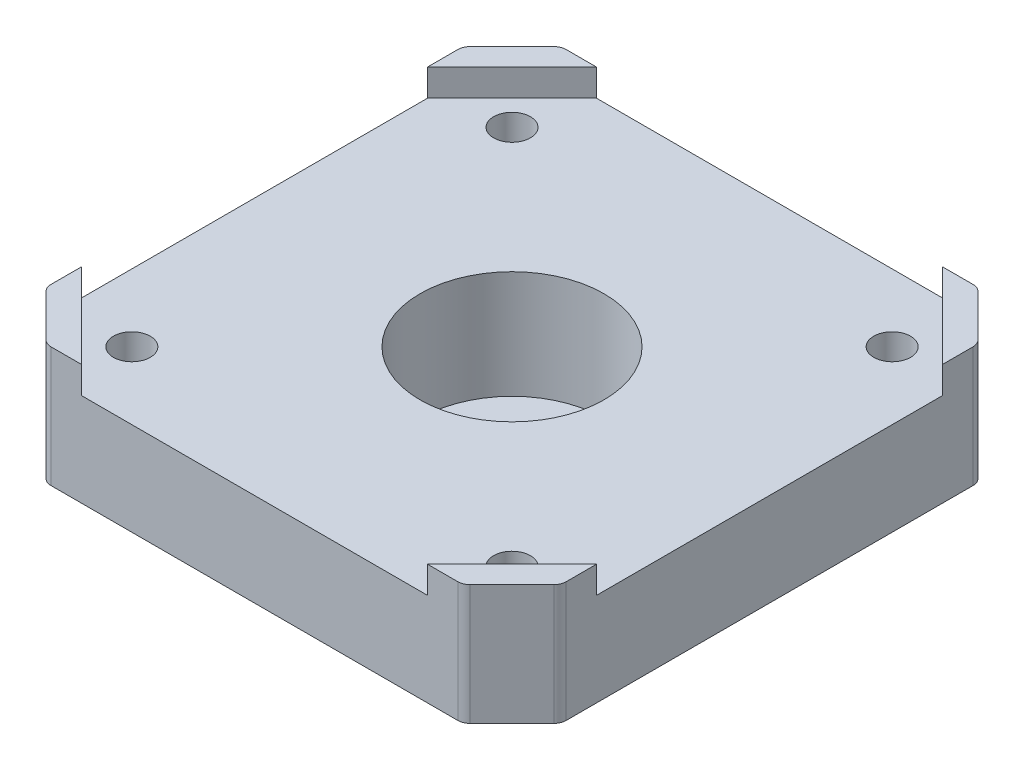
SolidWorks part; units mm, degrees
ref_plane "Alzado" through (0, 0, 0) normal (0, 0, 1) x (1, 0, 0)
ref_plane "Planta" through (0, 0, 0) normal (0, 1, 0) x (1, 0, 0)
ref_plane "Vista lateral" through (0, 0, 0) normal (1, 0, 0) x (0, 0, -1)
sketch "Croquis1" plane through (0, 0, 0) normal (0, 1, 0) x (1, 0, 0)
  line L0 (-21, 17) -> (-21, -17)
  line L1 (-21, -17) -> (-17, -21)
  line L2 (-17, -21) -> (17, -21)
  line L3 (17, -21) -> (21, -17)
  line L4 (21, -17) -> (21, 17)
  line L5 (21, 17) -> (17, 21)
  line L6 (17, 21) -> (-17, 21)
  line L7 (-17, 21) -> (-21, 17)
extrude "Saliente-Extruir1" add sketch "Croquis1" against normal blind 9.8
sketch "Croquis2" plane through (0, 0, 0) normal (0, 1, 0) x (-1, 0, 0)
  line L0 (-14.1008, -21) -> (14.1008, -21)
  line L1 (14.1008, -21) -> (21, -14.1008)
  line L2 (21, -14.1008) -> (21, 17)
  line L3 (21, 17) -> (17, 21)
  line L4 (17, 21) -> (-17, 21)
  line L5 (-17, 21) -> (-21, 17)
  line L6 (-21, 17) -> (-21, -14.1008)
  line L7 (-21, -14.1008) -> (-14.1008, -21)
extrude "Cortar-Extruir1" cut sketch "Croquis2" against normal blind 2.2
sketch "Croquis3" plane through (0, -2.2, 0) normal (0, 1, 0) x (-1, 0, 0)
  line L0 (-14.1008, 21) -> (-21, 14.1008)
  line L1 (-21, 14.1008) -> (-21, 17)
  line L2 (-21, 17) -> (-17, 21)
  line L3 (-17, 21) -> (-14.1008, 21)
extrude "Saliente-Extruir2" add sketch "Croquis3" along normal blind 2.2
sketch "Croquis4" plane through (0, -2.2, 0) normal (0, 1, 0) x (-1, 0, 0)
  line L0 (17, 21) -> (21, 17)
  line L1 (21, 17) -> (21, 14.1008)
  line L2 (21, 14.1008) -> (14.1008, 21)
  line L3 (14.1008, 21) -> (17, 21)
extrude "Saliente-Extruir3" add sketch "Croquis4" along normal blind 2.2
hole_wizard "Taladro de margen para M241" positions "Croquis6" profile "Croquis5" hole size "M24" standard "Ansi Metric"
sketch "Croquis6" plane through (0, -9.8, 0) normal (0, -1, 0) x (-1, 0, 0)
  point P0 (0, 0)
sketch "Croquis5" plane through (0, -9.8, 0) normal (1, 0, 0) x (0, 0, -1)
  line L0 (0, 0) -> (0, 0.3)
  line L1 (0, 0.3) -> (13.936, 0.3)
  line L2 (13.936, 0.3) -> (13.936, 0)
  line L5 (13.936, 0) -> (0, 0)
  line L10 (0, 0.3) -> (-13.936, 0.3) construction
  line L11 (0, -6.35) -> (0, 107.95) construction
  dimension "Diámetro de taladro" = 27.8721
  dimension "Profundidad de taladro" = 0.3
  dimension "Ángulo de perforador" = 180
sketch "Croquis7" plane through (0, 0, 0) normal (0, 0, 1) x (1, 0, 0)
  line L0 (10.5, -9.5) -> (0, -9.5)
  line L1 (0, -9.5) -> (0, -12.36)
  line L2 (0, -12.36) -> (10.5, -12.36)
  line L3 (10.5, -12.36) -> (10.5, -9.5)
  line L4 (0, -9.5) -> (0, -12.36) construction
revolve "Revolución1" add sketch "Croquis7" angle 360 about L4
hole_wizard "Refrentado para perno con cabeza hexagonal de M81" positions "Croquis9" profile "Croquis8" counterbore size "M8" standard "Ansi Metric"
sketch "Croquis9" plane through (0, -2.2, 0) normal (0, 1, 0) x (1, 0, 0)
  point P0 (0, 0)
sketch "Croquis8" plane through (0, -2.2, 0) normal (1, 0, 0) x (0, 0, 1)
  line L0 (0, 0) -> (0, 10.16)
  line L1 (0, 10.16) -> (4.225, 10.16)
  line L3 (4.225, 10.16) -> (4.225, 8.8)
  line L4 (4.225, 8.8) -> (7.5, 8.8)
  line L5 (7.5, 8.8) -> (7.5, 0)
  line L7 (7.5, 0) -> (0, 0)
  line L11 (0, -6.35) -> (0, 107.95) construction
  dimension "Diámetro de taladro hasta el siguiente" = 8.45
  dimension "Profundidad de taladro hasta el siguiente" = 10.16
  dimension "Diámetro de refrentado" = 15
  dimension "Profundidad de refrentado" = 8.8
hole_wizard "Diámetro de taladro Ø3.0 (3)1" positions "Croquis11" profile "Croquis10" hole size "Ø3.0" standard "Ansi Metric"
sketch "Croquis11" plane through (0, -2.2, 0) normal (0, 1, 0) x (1, 0, 0)
  point P0 (15.5, -15.5)
  point P1 (15.5, 15.5)
  point P2 (-15.5, -15.5)
  point P3 (-15.5, 15.5)
sketch "Croquis10" plane through (15.5, -2.2, 15.5) normal (1, 0, 0) x (0, 0, 1)
  line L0 (0, 0) -> (0, 10.16)
  line L1 (0, 10.16) -> (1.5, 10.16)
  line L2 (1.5, 10.16) -> (1.5, 0)
  line L5 (1.5, 0) -> (0, 0)
  line L11 (0, -6.35) -> (0, 107.95) construction
  dimension "Diámetro de taladro hasta el siguiente" = 3
  dimension "Profundidad de taladro hasta el siguiente" = 10.16
chamfer "Chaflán1" distance 0.25 angle 45 1 edges at (0, -12.36, 4.225)
fillet "Redondeo1" radius 1 8 edges at (-17, -4.9, 21) (-21, -4.9, -17) (-17, -4.9, -21) (17, -4.9, 21) (-21, -4.9, 17) (21, -4.9, 17) (21, -4.9, -17) (17, -4.9, -21)
